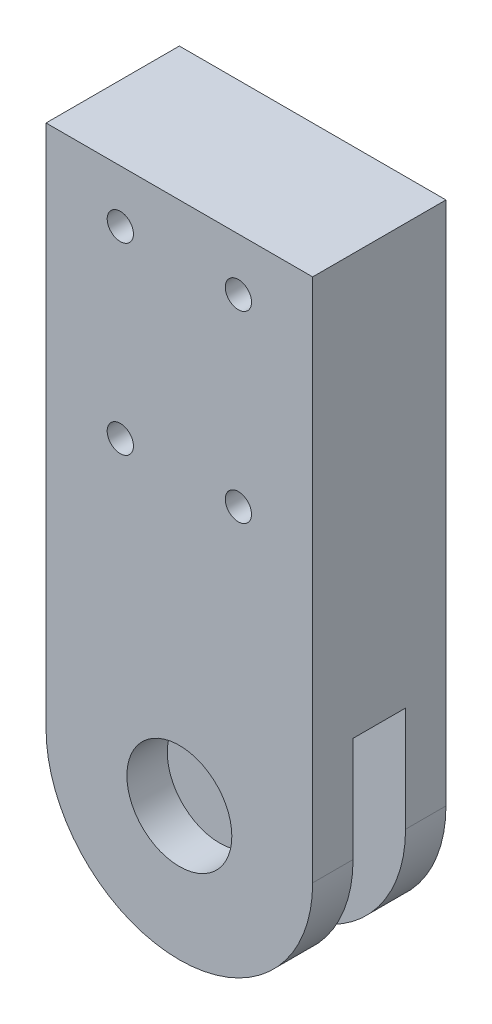
SolidWorks part; units mm, degrees
ref_plane "Front Plane" through (0, 0, 0) normal (0, 0, 1) x (1, 0, 0)
ref_plane "Top Plane" through (0, 0, 0) normal (0, 1, 0) x (1, 0, 0)
ref_plane "Right Plane" through (0, 0, 0) normal (1, 0, 0) x (0, 0, -1)
sketch "Sketch1" plane through (0, 0, 0) normal (0, 0, 1) x (1, 0, 0)
  line L2 (-25.4, 0) -> (-25.4, 100)
  line L4 (25.4, 0) -> (25.4, 100)
  line L7 (-25.4, 100) -> (25.4, 100)
  circle A1 centre (0, 0) radius 10
  arc A2 (-25.4, 0) -> (25.4, 0) centre (0, 0) ccw
  point P6 (0, 0)
  point P7 (0, 0)
  point P9 (0, 0)
  point P10 (0, 0)
  point P11 (-0.3941, -3.2517)
  point P13 (0, 0)
  dimension "D1" = 20
  dimension "D2" = 50.8
  dimension "D3" = 100
extrude "Boss-Extrude1" add sketch "Sketch1" along normal blind 25.4 contours L4 L7 L2 A2 | A1
sketch "Sketch2" plane through (-25.4, 0, 0) normal (-1, 0, 0) x (0, 0, 1)
  line L0 (0, -25.4) -> (25.4, -25.4) construction
  line L1 (7.7, 20) -> (17.7, 20)
  line L2 (7.7, 20) -> (7.7, -25.4)
  line L3 (7.7, -25.4) -> (17.7, -25.4)
  line L4 (17.7, 20) -> (17.7, -25.4)
  line L5 (25.4, 0) -> (0, 0) construction
  point P8 (12.7, 0)
  point P9 (12.7, 20)
  dimension "D1" = 20
  dimension "D2" = 10
extrude "Cut-Extrude1" cut sketch "Sketch2" against normal through all
sketch "Sketch3" plane through (0, 0, 25.4) normal (0, 0, 1) x (1, 0, 0)
  line L0 (-25.4, 100) -> (25.4, 100) construction
  line L1 (-11.25, 90) -> (11.25, 90) construction
  line L2 (-11.25, 90) -> (-11.25, 55) construction
  line L3 (-11.25, 55) -> (11.25, 55) construction
  line L4 (11.25, 90) -> (11.25, 55) construction
  circle A0 centre (-11.25, 90) radius 2.5
  circle A1 centre (11.25, 90) radius 2.5
  circle A2 centre (11.25, 55) radius 2.5
  circle A3 centre (-11.25, 55) radius 2.5
  point P5 (0, 55)
  point P12 (0, 0)
  dimension "D1" = 5
  dimension "D2" = 35
  dimension "D3" = 10
  dimension "D4" = 22.5
extrude "Cut-Extrude2" cut sketch "Sketch3" against normal through all
